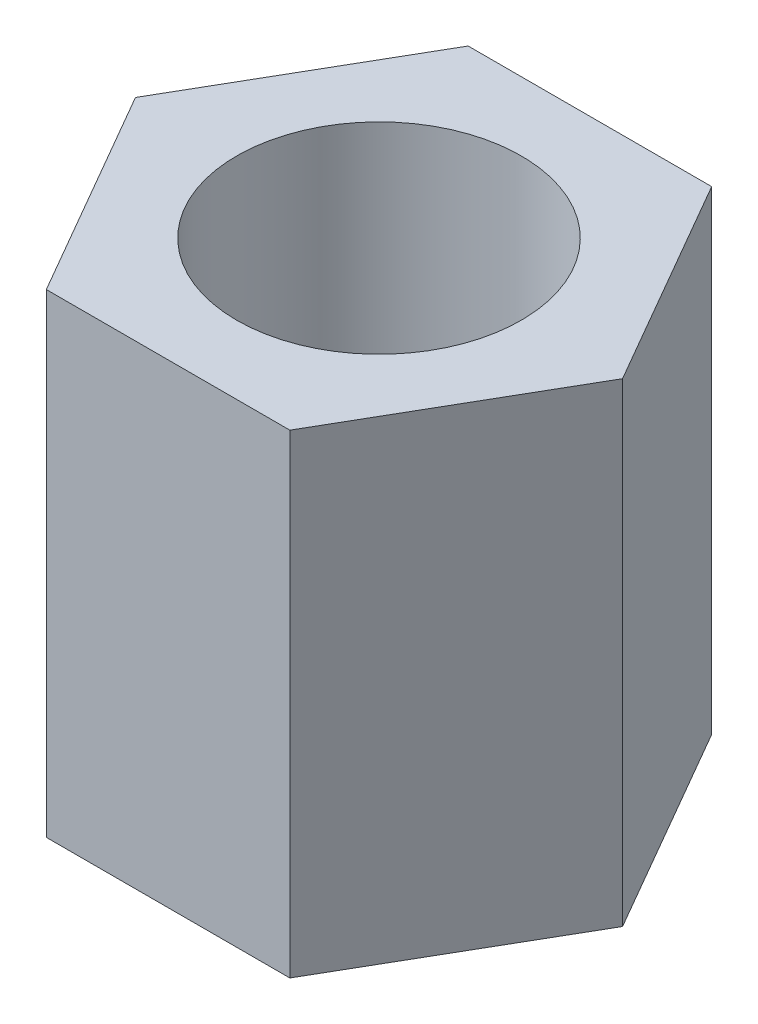
SolidWorks part; units mm, degrees
ref_plane "Front Plane" through (0, 0, 0) normal (0, 0, 1) x (1, 0, 0)
ref_plane "Top Plane" through (0, 0, 0) normal (0, 1, 0) x (1, 0, 0)
ref_plane "Right Plane" through (0, 0, 0) normal (1, 0, 0) x (0, 0, -1)
sketch "Sketch1" plane through (0, 0, 0) normal (0, 1, 0) x (1, 0, 0)
  line L7 (2.5665, 0) -> (1.2832, 2.2226)
  line L8 (1.2832, 2.2226) -> (-1.2832, 2.2226)
  line L9 (-1.2832, 2.2226) -> (-2.5665, 0)
  line L10 (-2.5665, 0) -> (-1.2832, -2.2226)
  line L11 (-1.2832, -2.2226) -> (1.2832, -2.2226)
  line L12 (1.2832, -2.2226) -> (2.5665, 0)
  circle A0 centre (0, 0) radius 1.5
  circle A1 centre (0, 0) radius 2.2226 construction
extrude "Boss-Extrude1" add sketch "Sketch1" along normal blind 5
